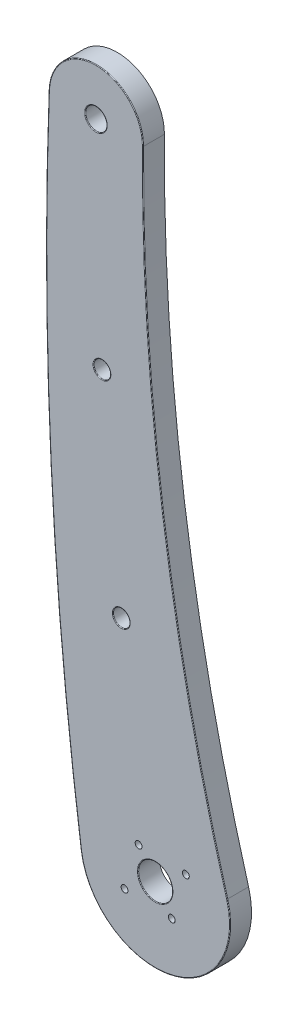
SolidWorks part; units mm, degrees
ref_plane "Front Plane" through (0, 0, 0) normal (0, 0, 1) x (1, 0, 0)
ref_plane "Top Plane" through (0, 0, 0) normal (0, 1, 0) x (1, 0, 0)
ref_plane "Right Plane" through (0, 0, 0) normal (1, 0, 0) x (0, 0, -1)
sketch "Sketch2" plane through (0, 0, 0) normal (0, 0, 1) x (1, 0, 0)
  line L0 (-20.22, 57.58) -> (-34.07, 204.9305) construction
  line L1 (-20.22, 57.58) -> (-34.07, 204.9305) construction
  circle A0 centre (-34.07, 204.9305) radius 11 construction
  circle A1 centre (-34.07, 204.9305) radius 11 construction
  circle A2 centre (-20.22, 57.58) radius 17.5 construction
  circle A3 centre (-20.22, 57.58) radius 17.5 construction
  circle A4 centre (-34.07, 204.9305) radius 2.5
  circle A5 centre (-20.22, 57.58) radius 4
  arc A6 (-23.0703, 204.8528) -> (-3.4086, 62.4407) centre (476.9172, 201.3188) ccw
  arc A7 (-45.0618, 205.3552) -> (-37.5523, 55.1634) centre (804.3045, 172.5393) ccw
  arc A8 (-34.07, 204.9305) -> (-20.22, 57.58) centre (715.9202, 201.0988) ccw construction
  arc A9 (-3.4086, 62.4407) -> (-37.5523, 55.1634) centre (-20.22, 57.58) cw
  arc A10 (-45.0618, 205.3552) -> (-23.0703, 204.8528) centre (-34.07, 204.9305) cw
  point P15 (-32.6587, 154.9504)
  point P16 (-28.1467, 106.9477)
  dimension "D1" = 5
  dimension "D2" = 8
  dimension "D3" = 850
  dimension "D4" = 500
  dimension "D5" = 750
  dimension "D6" = 50
  dimension "D7" = 50
extrude "Boss-Extrude1" add sketch "Sketch2" against normal blind 5
hole_wizard "M3.5 Clearance Hole1" positions "Sketch4" profile "Sketch3" hole size "M3.5" standard "ISO"
sketch "Sketch4" plane through (0, 0, 0) normal (0, 0, 1) x (1, 0, 0)
  point P0 (-32.6587, 154.9504)
  point P3 (-28.1467, 106.9477)
sketch "Sketch3" plane through (-32.6587, 154.9504, 0) normal (1, 0, 0) x (0, -1, 0)
  line L0 (0, 0) -> (0, 11.1717)
  line L1 (0, 11.1717) -> (1.95, 10)
  line L2 (1.95, 10) -> (1.95, 0)
  line L5 (1.95, 0) -> (0, 0)
  line L10 (0, 11.1717) -> (-1.95, 10) construction
  line L11 (0, -6.35) -> (0, 107.95) construction
  dimension "Hole Dia." = 3.9
  dimension "Hole Depth" = 10
  dimension "Drill Angle" = 118
fillet "Fillet1" radius 0.15 8 edges at (-18.3846, 132.9364, 0) (-16.572, 40.4644, 0) (-44.635, 130.0929, 0) (-33.8188, 215.9277, 0) (-31.57, 204.9305, 0) (-16.22, 57.58, 0) (-26.1967, 106.9477, 0) (-30.7087, 154.9504, 0)
sketch "Sketch8" plane through (0, 0, 0) normal (0, 0, 1) x (1, 0, 0)
  circle A0 centre (-13.0565, 62.6046) radius 0.8
  circle A1 centre (-24.0961, 63.1061) radius 0.8
  circle A2 centre (-27.3835, 52.5554) radius 0.8
  circle A3 centre (-16.3439, 52.0539) radius 0.8
  dimension "D1" = 1.6
  dimension "D6" = 1.6
  dimension "D2" = 7.5082
  dimension "D3" = 28.5681
  dimension "D4" = 150.1653
  dimension "D5" = 3.1303
  dimension "D7" = 17.5284
  dimension "D8" = 20.8158
  dimension "D9" = 31.8555
  dimension "D10" = 7.4205
  dimension "D11" = 7.922
  dimension "D12" = 2.6288
extrude "Cut-Extrude1" cut sketch "Sketch8" against normal through all contours A2 | A3 | A0 | A1
